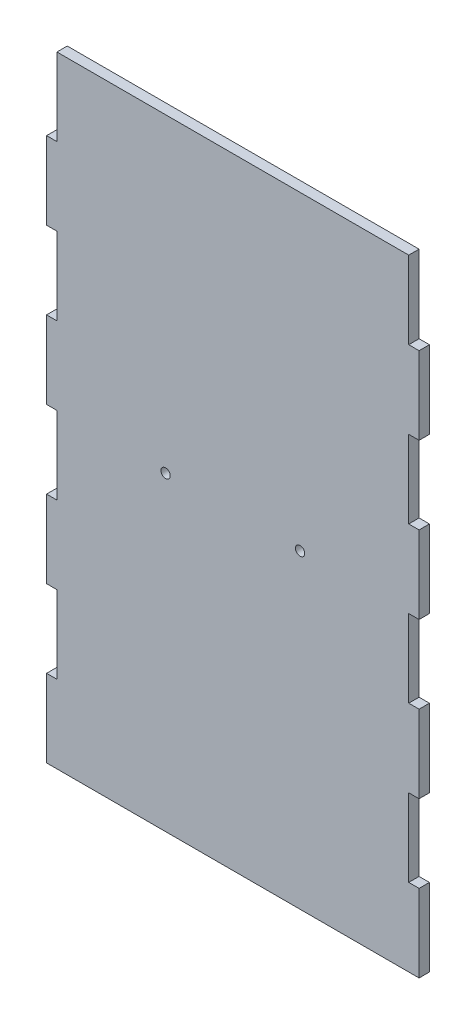
SolidWorks part; units mm, degrees
ref_plane "Front Plane" through (0, 0, 0) normal (0, 0, 1) x (1, 0, 0)
ref_plane "Top Plane" through (0, 0, 0) normal (0, 1, 0) x (1, 0, 0)
ref_plane "Right Plane" through (0, 0, 0) normal (1, 0, 0) x (0, 0, -1)
sketch "Sketch1" plane through (0, 0, 0) normal (0, 0, 1) x (1, 0, 0)
  line L1 (-90, 0) -> (90, 0)
  line L2 (-90, 0) -> (-90, 300)
  line L3 (-90, 300) -> (90, 300)
  line L4 (90, 0) -> (90, 300)
  line L5 (-90, 0) -> (90, 300) construction
  line L6 (-90, 300) -> (90, 0) construction
  circle A0 centre (-32.5, 150) radius 2.25
  circle A1 centre (32.5, 150) radius 2.25
  point P0 (0, 150)
  dimension "D3" = 4.5
  dimension "D1" = 300
  dimension "D2" = 180
extrude "Boss-Extrude1" add sketch "Sketch1" along normal blind 5
sketch "Sketch2" plane through (0, 0, 5) normal (0, 0, 1) x (1, 0, 0)
  line L0 (-90, 300) -> (-90, 0) construction
  line L1 (-90, 300) -> (-85, 300)
  line L2 (-90, 300) -> (-90, 262.5)
  line L3 (-90, 262.5) -> (-85, 262.5)
  line L4 (-85, 300) -> (-85, 262.5)
  line L5 (-90, 225) -> (-85, 225)
  line L6 (-90, 225) -> (-90, 187.5)
  line L7 (-90, 187.5) -> (-85, 187.5)
  line L8 (-85, 225) -> (-85, 187.5)
  line L9 (90, 0) -> (90, 300) construction
  line L10 (-90, 150) -> (-85, 150)
  line L11 (-90, 150) -> (-90, 112.5)
  line L12 (-90, 112.5) -> (-85, 112.5)
  line L13 (-85, 150) -> (-85, 112.5)
  line L14 (-90, 75) -> (-85, 75)
  line L15 (-90, 75) -> (-90, 37.5)
  line L16 (-90, 37.5) -> (-85, 37.5)
  line L17 (-85, 75) -> (-85, 37.5)
  line L18 (90, 300) -> (85, 300)
  line L19 (90, 300) -> (90, 262.5)
  line L20 (90, 262.5) -> (85, 262.5)
  line L21 (85, 300) -> (85, 262.5)
  line L22 (90, 300) -> (-90, 300) construction
  line L23 (85, 262.5) -> (85, 225) construction
  line L24 (90, 225) -> (85, 225)
  line L25 (90, 225) -> (90, 187.5)
  line L26 (90, 187.5) -> (85, 187.5)
  line L27 (85, 225) -> (85, 187.5)
  line L28 (90, 150) -> (85, 150)
  line L29 (90, 150) -> (90, 112.5)
  line L30 (90, 112.5) -> (85, 112.5)
  line L31 (85, 150) -> (85, 112.5)
  line L32 (90, 75) -> (85, 75)
  line L33 (90, 75) -> (90, 37.5)
  line L34 (90, 37.5) -> (85, 37.5)
  line L35 (85, 75) -> (85, 37.5)
  line L36 (85, 187.5) -> (85, 150) construction
  line L37 (85, 112.5) -> (85, 75) construction
  line L38 (85, 75) -> (85.0693, 74.2781) construction
  line L39 (85, 37.5) -> (85, 0) construction
  line L40 (-90, 0) -> (90, 0) construction
  line L41 (-85, 262.5) -> (-85, 225) construction
  line L42 (-85, 225) -> (-85.1311, 225.9205) construction
  line L43 (-85, 187.5) -> (-85, 150) construction
  line L44 (-85, 112.5) -> (-85, 75) construction
  line L45 (-85, 37.5) -> (-85, 0) construction
  dimension "D1" = 5
extrude "Cut-Extrude1" cut sketch "Sketch2" against normal up to next
